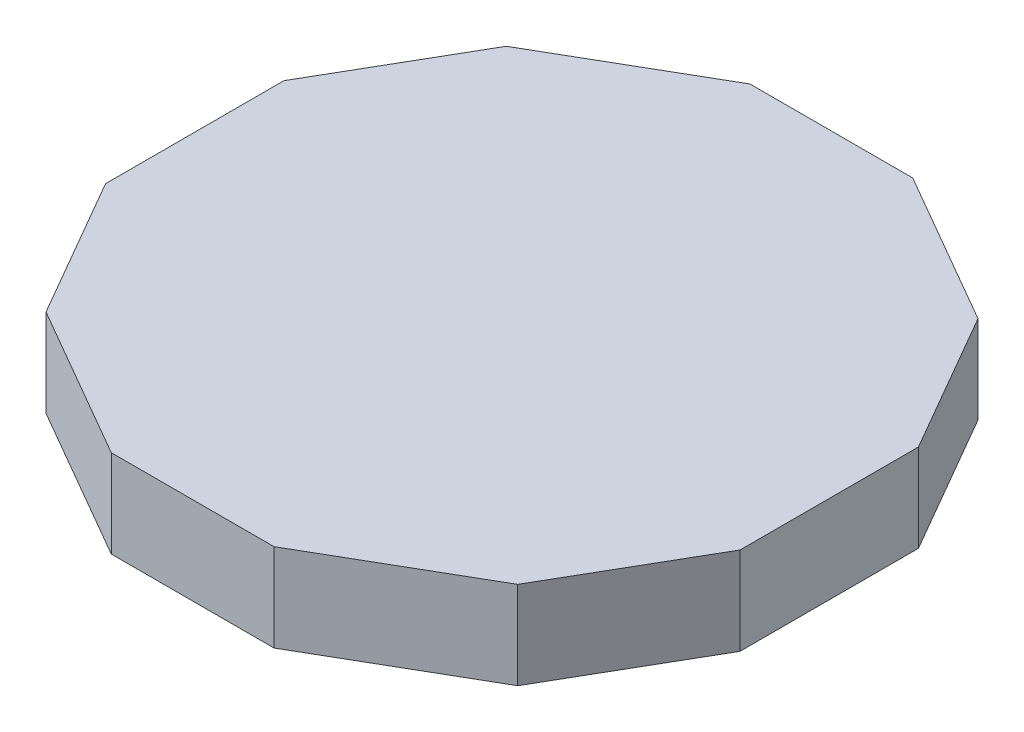
SolidWorks part; units mm, degrees
ref_plane "前视基准面" through (0, 0, 0) normal (0, 0, 1) x (1, 0, 0)
ref_plane "上视基准面" through (0, 0, 0) normal (0, 1, 0) x (1, 0, 0)
ref_plane "右视基准面" through (0, 0, 0) normal (1, 0, 0) x (0, 0, -1)
sketch "草图4" plane through (0, 0, 0) normal (0, 1, 0) x (1, 0, 0)
  line L0 (336.0179, 0) -> (-336.0179, 0) construction
  line L1 (-336.0179, 0) -> (-168.0089, -291)
  line L2 (-168.0089, -291) -> (168.0089, -291)
  line L3 (168.0089, -291) -> (336.0179, 0)
  line L4 (336.0179, 0) -> (168.0089, 291)
  line L5 (168.0089, 291) -> (-168.0089, 291)
  line L6 (-168.0089, 291) -> (-336.0179, 0)
  line L7 (289.0885, 81.284) -> (289.0885, -81.284)
  line L8 (214.9383, -209.716) -> (74.1502, -291)
  line L9 (-74.1502, -291) -> (-214.9383, -209.716)
  line L10 (-289.0885, -81.284) -> (-289.0885, 81.284)
  line L11 (-214.9383, 209.716) -> (-74.1502, 291)
  line L12 (74.1502, 291) -> (214.9383, 209.716)
  line L13 (0, 0) -> (289.0885, -81.284) construction
  line L14 (-74.1502, 291) -> (168.0089, 291)
  line L15 (74.1502, 291) -> (-74.1502, 291)
  line L16 (289.0885, 81.284) -> (214.9383, 209.716)
  line L17 (214.9383, -209.716) -> (289.0885, -81.284)
  line L18 (-74.1502, -291) -> (74.1502, -291)
  line L19 (-289.0885, -81.284) -> (-214.9383, -209.716)
  line L20 (-214.9383, 209.716) -> (-289.0885, 81.284)
  line L21 (0, 0) -> (74.1502, 291) construction
  dimension "D1" = 582
  dimension "D3" = 300.2986
  dimension "D5" = 300.2986
  dimension "D2" = 6
  dimension "D4" = 6
extrude "凸台-拉伸1" add sketch "草图4" along normal blind 80 contours L12 L5 L11 L6 L10 L1 L9 L2 L8 L3 L7 L4
